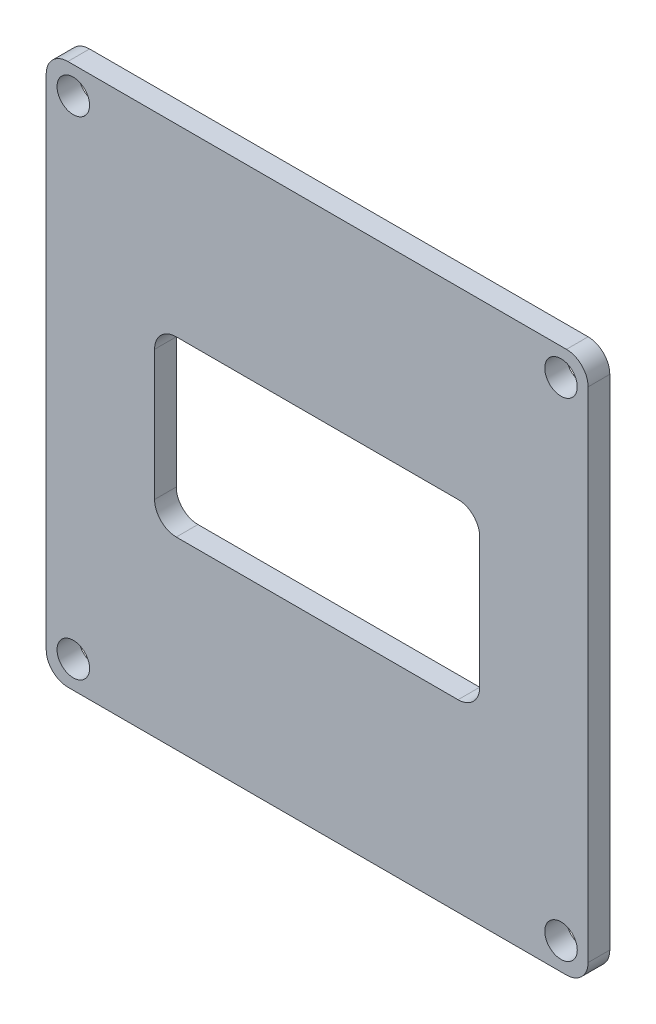
SolidWorks part; units mm, degrees
ref_plane "前视基准面" through (0, 0, 0) normal (0, 0, 1) x (1, 0, 0)
ref_plane "上视基准面" through (0, 0, 0) normal (0, 1, 0) x (1, 0, 0)
ref_plane "右视基准面" through (0, 0, 0) normal (1, 0, 0) x (0, 0, -1)
sketch "草图1" plane through (0, 0, 0) normal (0, 0, 1) x (1, 0, 0)
  line L0 (4.4689, 8.8421) -> (4.4689, -21.9615) construction
  line L1 (-20.5311, 25.8421) -> (29.4689, 25.8421)
  line L2 (-20.5311, 25.8421) -> (-20.5311, -24.1579)
  line L3 (-20.5311, -24.1579) -> (29.4689, -24.1579)
  line L4 (29.4689, 25.8421) -> (29.4689, -24.1579)
  line L5 (-10.5311, 8.8421) -> (19.4689, 8.8421)
  line L6 (-10.5311, 8.8421) -> (-10.5311, -7.1579)
  line L7 (-10.5311, -7.1579) -> (19.4689, -7.1579)
  line L8 (19.4689, 8.8421) -> (19.4689, -7.1579)
  line L9 (-10.5311, 0.8421) -> (19.4689, 0.8421) construction
  circle A0 centre (-18.0311, 23.3421) radius 1.5
  circle A1 centre (26.9689, 23.3421) radius 1.5
  circle A2 centre (26.9689, -21.6579) radius 1.5
  circle A3 centre (-18.0311, -21.6579) radius 1.5
  dimension "D7" = 2.5
  dimension "D1" = 50
  dimension "D2" = 50
  dimension "D3" = 30
  dimension "D4" = 17
  dimension "D5" = 17
  dimension "D6" = 10
  dimension "D8" = 2.5
extrude "凸台-拉伸1" add sketch "草图1" along normal blind 2
fillet "圆角1" radius 2 1 edges at (19.4689, 8.8421, 1)
fillet "圆角2" radius 2 1 edges at (19.4689, -7.1579, 1)
fillet "圆角3" radius 2 1 edges at (-10.5311, 8.8421, 1)
fillet "圆角4" radius 2 1 edges at (-10.5311, -7.1579, 1)
fillet "圆角5" radius 2 1 edges at (29.4689, 25.8421, 1)
fillet "圆角6" radius 2 1 edges at (29.4689, -24.1579, 1)
fillet "圆角7" radius 2 1 edges at (-20.5311, 25.8421, 1)
fillet "圆角8" radius 2 1 edges at (-20.5311, -24.1579, 1)
